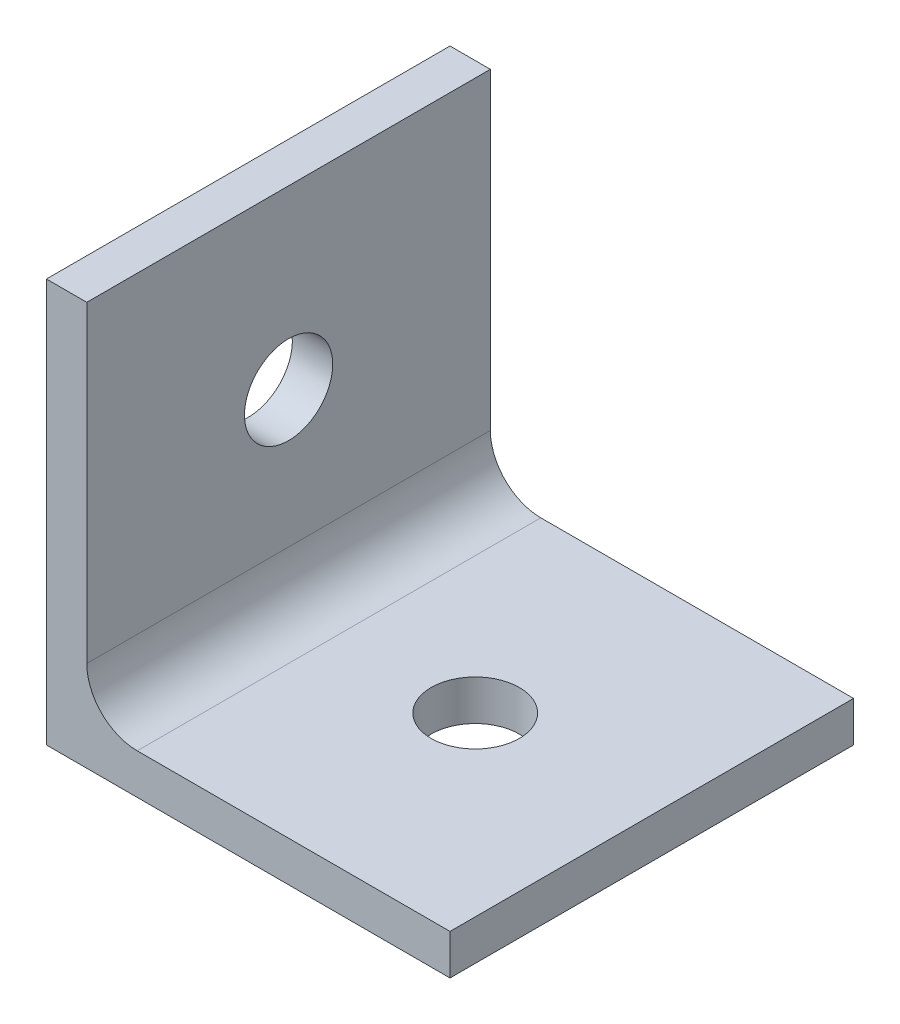
SolidWorks part; units mm, degrees
material "6061-T6 (SS)"
ref_plane "Ebene vorne" through (0, 0, 0) normal (0, 0, 1) x (1, 0, 0)
ref_plane "Ebene oben" through (0, 0, 0) normal (0, 1, 0) x (1, 0, 0)
ref_plane "Ebene rechts" through (0, 0, 0) normal (1, 0, 0) x (0, 0, -1)
sketch "Skizze1" plane through (0, 0, 0) normal (0, 0, 1) x (1, 0, 0)
  line L0 (0, 0) -> (80, 0)
  line L1 (80, 0) -> (80, 8)
  line L2 (80, 8) -> (18, 8)
  line L3 (8, 18) -> (8, 80)
  line L4 (8, 80) -> (0, 80)
  line L5 (0, 80) -> (0, 0)
  arc A0 (18, 8) -> (8, 18) centre (18, 18) cw
  dimension "D5" = 10
  dimension "D1" = 8
  dimension "D2" = 8
  dimension "D3" = 80
  dimension "D4" = 80
extrude "Aufsatz Auftragen Main Body" add sketch "Skizze1" along normal mid plane 80
sketch "Skizze3" plane through (0, 8, 0) normal (0, 1, 0) x (1, 0, 0)
  line L0 (0, -40) -> (0, 40) construction
  circle A0 centre (45, 0) radius 8.75
  dimension "D1" = 17.5
  dimension "D2" = 45
extrude "Bohrung Horizontal" cut sketch "Skizze3" against normal through all
sketch "Skizze4" plane through (8, 0, 0) normal (1, 0, 0) x (0, 0, -1)
  line L1 (-40, 0) -> (40, 0) construction
  circle A0 centre (0, 45) radius 8.75
  dimension "D1" = 17.5
  dimension "D2" = 45
other "AusrichtungGruppe1"
extrude "Bohrung Vertikal" cut sketch "Skizze4" against normal through all
